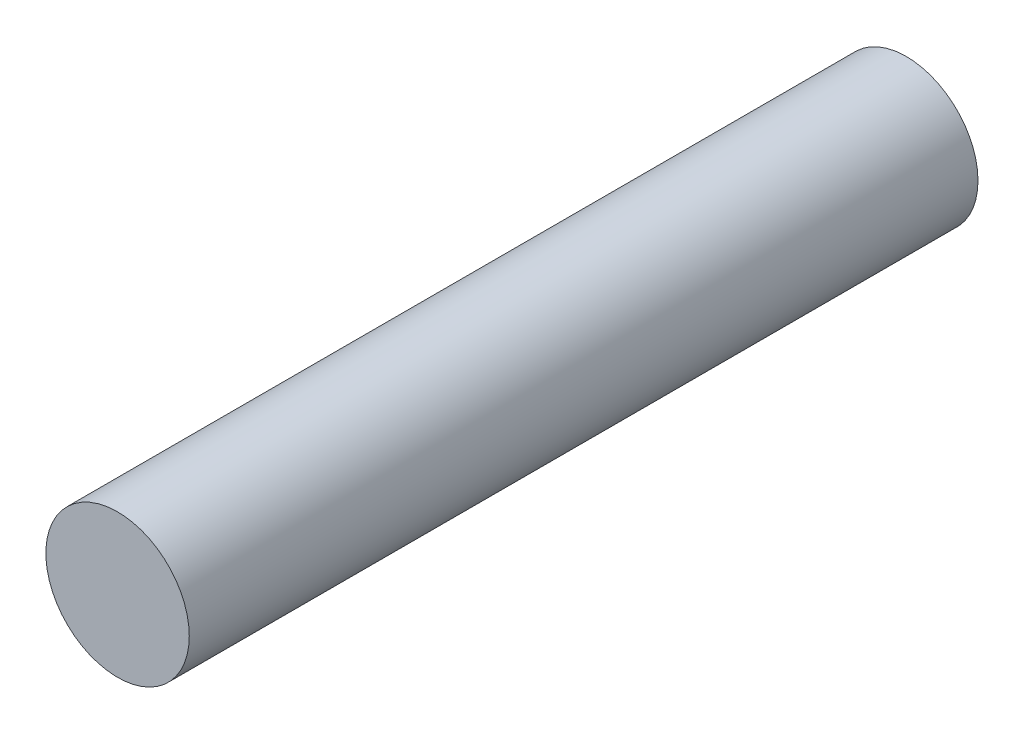
SolidWorks part; units mm, degrees
material "Brass"
ref_plane "Front Plane" through (0, 0, 0) normal (0, 0, 1) x (1, 0, 0)
ref_plane "Top Plane" through (0, 0, 0) normal (0, 1, 0) x (1, 0, 0)
ref_plane "Right Plane" through (0, 0, 0) normal (1, 0, 0) x (0, 0, -1)
sketch "Sketch1" plane through (0, 0, 0) normal (0, 0, 1) x (1, 0, 0)
  circle A0 centre (0, 0) radius 1
  dimension "Pin Diameter" = 2
extrude "Boss-Extrude1" add sketch "Sketch1" along normal blind 11
